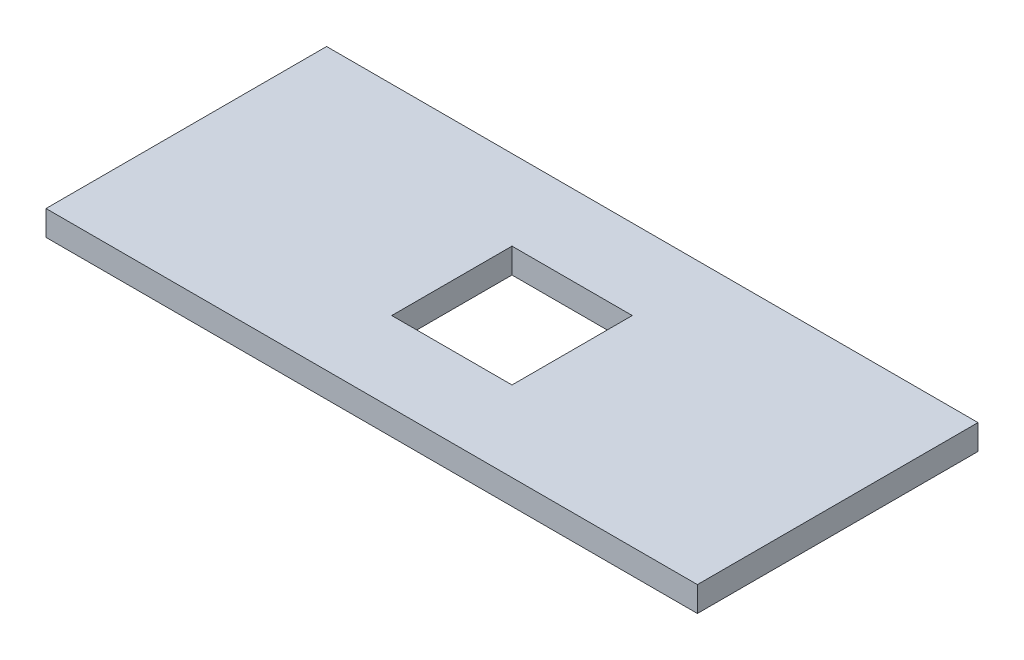
SolidWorks part; units mm, degrees
ref_plane "Ön Düzlem" through (0, 0, 0) normal (0, 0, 1) x (1, 0, 0)
ref_plane "Üst Düzlem" through (0, 0, 0) normal (0, 1, 0) x (1, 0, 0)
ref_plane "Sağ Düzlem" through (0, 0, 0) normal (1, 0, 0) x (0, 0, -1)
sketch "Çizim1" plane through (0, 0, 0) normal (0, 1, 0) x (1, 0, 0)
  line L1 (-65, -28) -> (65, -28)
  line L2 (-65, -28) -> (-65, 28)
  line L3 (-65, 28) -> (65, 28)
  line L4 (65, -28) -> (65, 28)
  line L5 (0, 28) -> (0, -28) construction
  line L6 (-65, 0) -> (65, 0) construction
  line L7 (-12, -12) -> (12, -12)
  line L8 (-12, -12) -> (-12, 12)
  line L9 (-12, 12) -> (12, 12)
  line L10 (12, -12) -> (12, 12)
  line L11 (0, 12) -> (0, -12) construction
  line L12 (-12, 0) -> (12, 0) construction
  point P0 (0, 0)
  point P4 (0, 0)
  dimension "D1" = 130
  dimension "D2" = 56
  dimension "D3" = 24
  dimension "D4" = 24
extrude "Yükseklik-Ekstrüzyon1" add sketch "Çizim1" along normal blind 5
